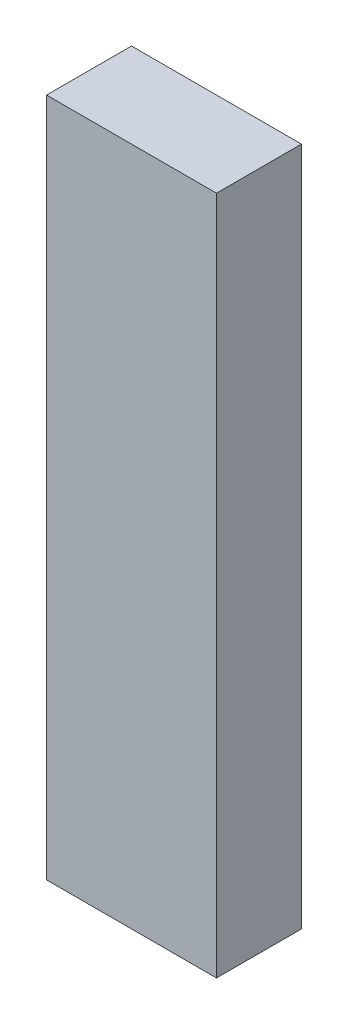
SolidWorks part; units mm, degrees
ref_plane "Plan de face" through (0, 0, 0) normal (0, 0, 1) x (1, 0, 0)
ref_plane "Plan de dessus" through (0, 0, 0) normal (0, 1, 0) x (1, 0, 0)
ref_plane "Plan de droite" through (0, 0, 0) normal (1, 0, 0) x (0, 0, -1)
sketch "Esquisse1" plane through (0, 0, 0) normal (0, 0, 1) x (1, 0, 0)
  line L1 (0, 0) -> (10, 0)
  line L2 (0, 0) -> (0, 40)
  line L3 (0, 40) -> (10, 40)
  line L4 (10, 0) -> (10, 40)
  dimension "D1" = 10
  dimension "D2" = 40
extrude "Boss.-Extru.1" add sketch "Esquisse1" along normal blind 5
